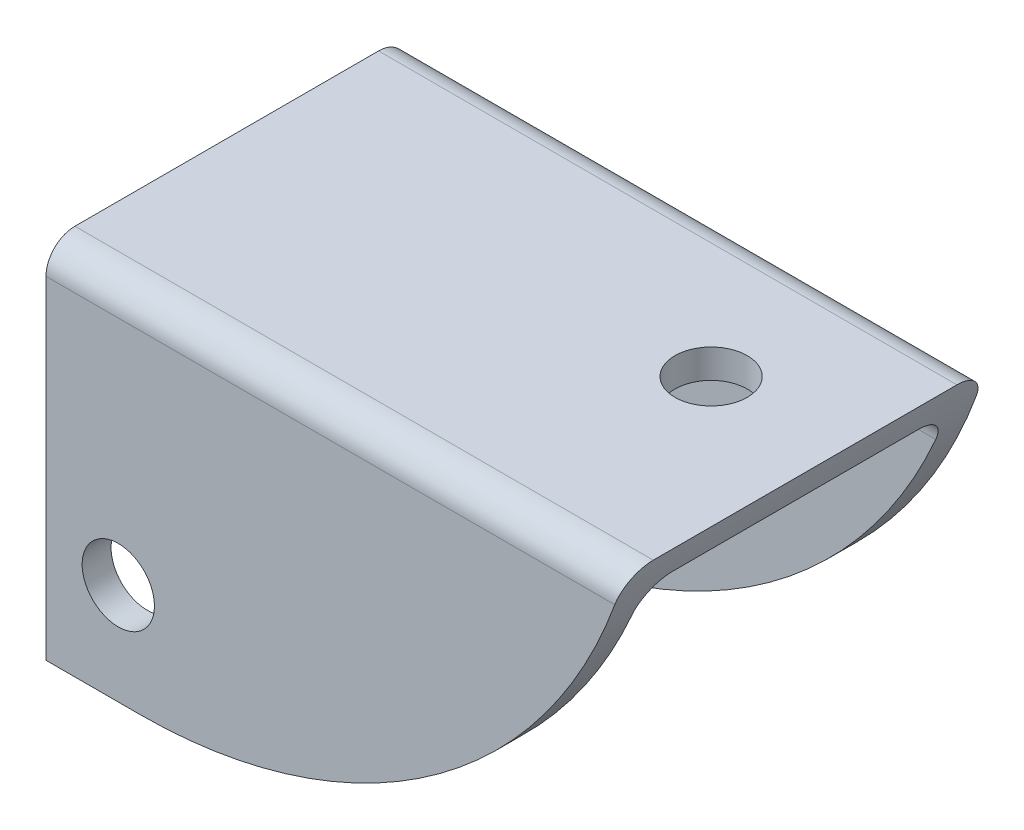
SolidWorks part; units mm, degrees
ref_plane "前视基准面" through (0, 0, 0) normal (0, 0, 1) x (1, 0, 0)
ref_plane "上视基准面" through (0, 0, 0) normal (0, 1, 0) x (1, 0, 0)
ref_plane "右视基准面" through (0, 0, 0) normal (1, 0, 0) x (0, 0, -1)
sketch "草图1" plane through (0, 0, 0) normal (1, 0, 0) x (0, 0, -1)
  line L0 (0, 0) -> (0, 25)
  line L1 (0, 25) -> (25, 25)
  line L2 (25, 25) -> (25, 0)
  line L3 (2, 0) -> (2, 23)
  line L4 (2, 23) -> (23, 23)
  line L5 (23, 23) -> (23, 0)
  line L6 (2, 0) -> (0, 0)
  line L7 (23, 0) -> (25, 0)
  dimension "D1" = 25
  dimension "D2" = 25
  dimension "D3" = 2
extrude "凸台-拉伸1" add sketch "草图1" along normal blind 40
sketch "草图3" plane through (0, 0, 0) normal (0, 0, 1) x (1, 0, 0)
  line L0 (40, 0) -> (0, 0) construction
  line L1 (40, 25) -> (40, 0)
  line L2 (40, 0) -> (6.459, 0)
  arc A0 (40, 25) -> (6.459, 0) centre (6.459, 35) cw
  dimension "D1" = 35
extrude "切除-拉伸1" cut sketch "草图3" against normal blind 40
sketch "草图4" plane through (0, 25, 0) normal (0, 1, 0) x (1, 0, 0)
  line L0 (0, 25) -> (0, 0) construction
  line L1 (40, 25) -> (0, 25) construction
  circle A0 centre (31, 15) radius 2.5
  dimension "D1" = 5
  dimension "D2" = 31
  dimension "D3" = 10
extrude "切除-拉伸2" cut sketch "草图4" against normal through all
sketch "草图5" plane through (0, 0, 0) normal (0, 0, 1) x (1, 0, 0)
  line L0 (0, 25) -> (0, 0) construction
  line L1 (40, 25) -> (0, 25) construction
  circle A0 centre (5, 7) radius 2.5
  dimension "D1" = 5
  dimension "D2" = 5
  dimension "D3" = 18
extrude "切除-拉伸3" cut sketch "草图5" against normal through all
fillet "圆角1" radius 2 4 edges at (20, 25, -25) (20, 25, 0) (19.6688, 23, -2) (19.6688, 23, -23)
